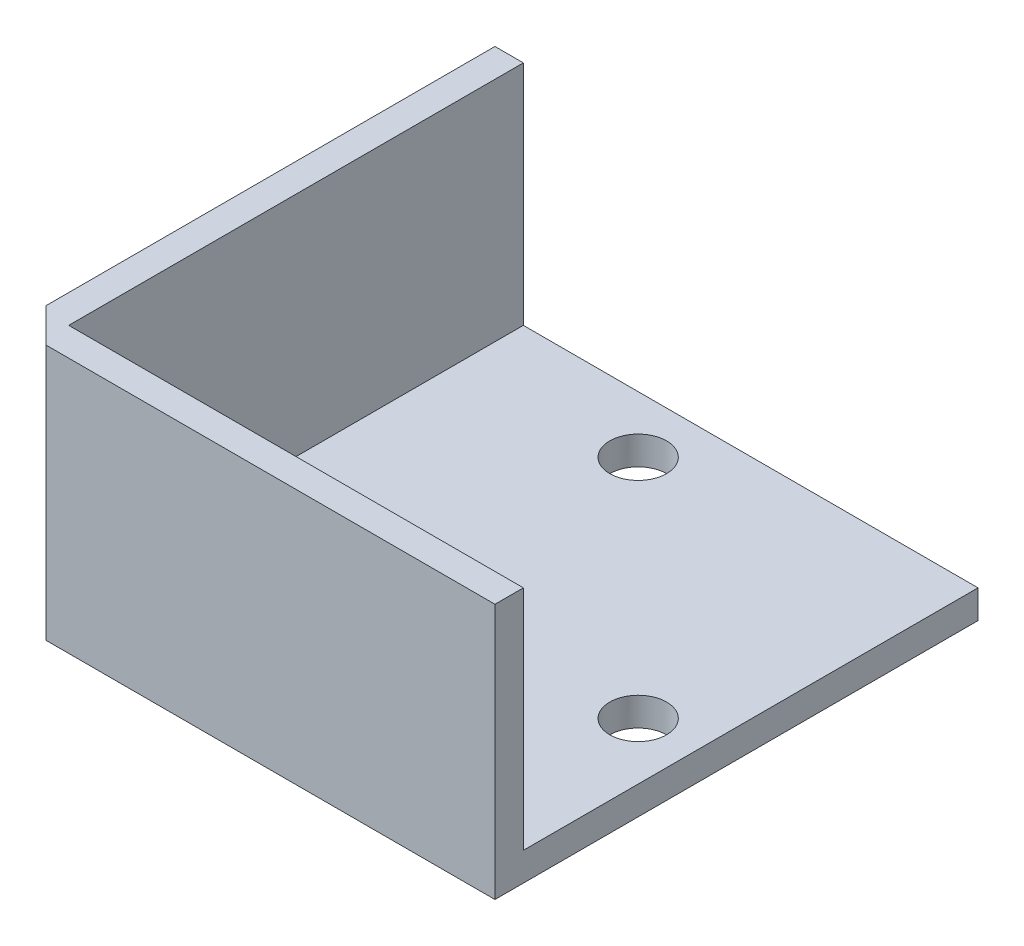
SolidWorks part; units mm, degrees
ref_plane "Front Plane" through (0, 0, 0) normal (0, 0, 1) x (1, 0, 0)
ref_plane "Top Plane" through (0, 0, 0) normal (0, 1, 0) x (1, 0, 0)
ref_plane "Right Plane" through (0, 0, 0) normal (1, 0, 0) x (0, 0, -1)
sketch "Sketch1" plane through (0, 0, 0) normal (0, 1, 0) x (1, 0, 0)
  line L1 (0, 0) -> (53.975, 0)
  line L2 (0, 0) -> (0, 53.975)
  line L3 (0, 53.975) -> (53.975, 53.975)
  line L4 (53.975, 0) -> (53.975, 53.975)
  dimension "D1" = 53.975
  dimension "D2" = 53.975
extrude "Boss-Extrude1" add sketch "Sketch1" along normal blind 3.175
sketch "Sketch2" plane through (0, 3.175, 0) normal (0, 1, 0) x (1, 0, 0)
  line L0 (0, 53.975) -> (0, 0)
  line L1 (0, 53.975) -> (3.175, 53.975)
  line L2 (0, 0) -> (3.175, 0)
  line L3 (3.175, 53.975) -> (3.175, 0)
  line L4 (0, 0) -> (53.975, 0)
  line L5 (0, 0) -> (0, 3.175)
  line L6 (53.975, 0) -> (53.975, 3.175)
  line L7 (0, 3.175) -> (53.975, 3.175)
  line M5 (0, 53.975) -> (0, 0)
  line M6 (0, 0) -> (53.975, 0)
  line M7 (53.975, 0) -> (53.975, 53.975)
  line M8 (53.975, 53.975) -> (0, 53.975)
  dimension "D1" = 3.175
  dimension "D2" = 3.175
extrude "Boss-Extrude2" add sketch "Sketch2" along normal blind 25.4 contours L7 L3 M5 M8 | L7 L3 M6 M7 | L7 L0 L3 M6
chamfer "Chamfer1" distance 3.81 angle 45 1 edges at (0, 14.2875, 0)
sketch "Sketch3" plane through (0, 3.175, 0) normal (0, 1, 0) x (1, 0, 0)
  line L0 (53.975, 3.175) -> (53.975, 53.975) construction
  line L1 (53.975, 53.975) -> (3.175, 53.975) construction
  line L2 (0, 53.975) -> (0, 3.81) construction
  line L3 (3.81, 0) -> (53.975, 0) construction
  circle A0 centre (22.352, 47.625) radius 3.175
  circle A1 centre (47.625, 22.352) radius 3.175
  point P4 (0, 0)
  dimension "D1" = 6.35
  dimension "D2" = 6.35
  dimension "D3" = 6.35
  dimension "D4" = 6.35
  dimension "D5" = 22.352
  dimension "D6" = 22.352
extrude "Cut-Extrude1" cut sketch "Sketch3" against normal blind 25.4
